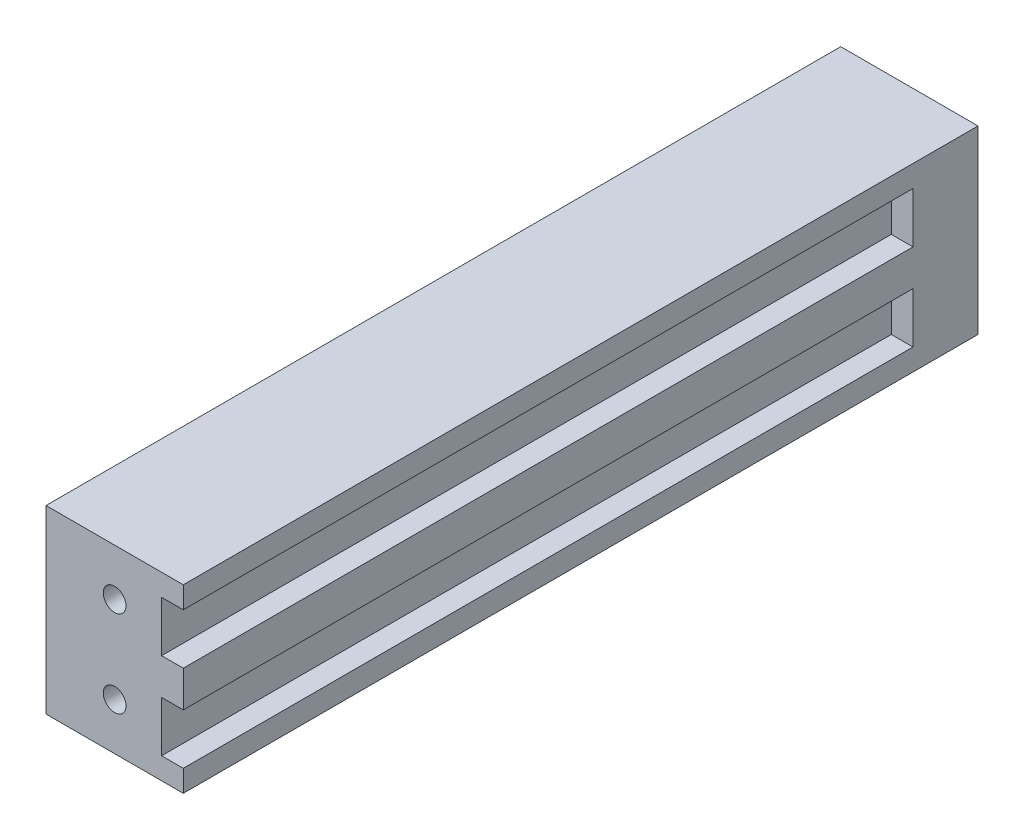
SolidWorks part; units mm, degrees
ref_plane "Ebene vorne" through (0, 0, 0) normal (0, 0, 1) x (1, 0, 0)
ref_plane "Ebene oben" through (0, 0, 0) normal (0, 1, 0) x (1, 0, 0)
ref_plane "Ebene rechts" through (0, 0, 0) normal (1, 0, 0) x (0, 0, -1)
sketch "Sketch1" plane through (0, 0, 0) normal (0, 1, 0) x (1, 0, 0)
  line L1 (9.5, -55) -> (-9.5, -55)
  line L2 (9.5, -55) -> (9.5, 55)
  line L3 (9.5, 55) -> (-9.5, 55)
  line L4 (-9.5, -55) -> (-9.5, 55)
  line L5 (9.5, -55) -> (-9.5, 55) construction
  line L6 (9.5, 55) -> (-9.5, -55) construction
  point P0 (0, 0)
  dimension "D1" = 19
  dimension "D2" = 110
extrude "Block" add sketch "Sketch1" along normal blind 25
sketch "Sketch2" plane through (9.5, 0, 0) normal (1, 0, 0) x (0, 0, -1)
  line L0 (-55, 25) -> (-55, 0) construction
  line L1 (-55, 10) -> (46, 10)
  line L2 (-55, 10) -> (-55, 3)
  line L3 (-55, 3) -> (46, 3)
  line L4 (46, 10) -> (46, 3)
  line L5 (-55, 25) -> (55, 25) construction
  line L6 (-55, 0) -> (55, 0) construction
  line L7 (-55, 22) -> (46, 22)
  line L8 (-55, 22) -> (-55, 15)
  line L9 (-55, 15) -> (46, 15)
  line L10 (46, 22) -> (46, 15)
  dimension "D1" = 7
  dimension "D2" = 3
  dimension "D3" = 3
  dimension "D4" = 101
extrude "Slides" cut sketch "Sketch2" against normal blind 3
sketch "Sketch3" plane through (-9.5, 0, 0) normal (-1, 0, 0) x (0, 0, 1)
  line L0 (55, 25) -> (55, 0) construction
  line L2 (-55, 0) -> (55, 0) construction
  circle A0 centre (-50, 6) radius 1.5
  circle A1 centre (51, 6) radius 1.5
  dimension "D2" = 3
  dimension "D1" = 101
  dimension "D3" = 4
  dimension "D4" = 6
extrude "Mounting Holes" cut sketch "Sketch3" against normal blind 10
sketch "Sketch5" plane through (0, 0, 55) normal (0, 0, 1) x (1, 0, 0)
  line L0 (0, 25) -> (0, 0) construction
  line L1 (-9.5, 0) -> (9.5, 0) construction
  line L3 (-9.5, 25) -> (9.5, 25) construction
  line L4 (0, 12.5) -> (-5.3784, 12.5) construction
  circle A0 centre (0, 18.5) radius 1.575
  circle A1 centre (0, 6.5) radius 1.575
  dimension "D1" = 3.15
  dimension "D2" = 6
extrude "Cut-Extrude1" cut sketch "Sketch5" against normal blind 15 draft 1
equation "\"PCB\"=98"
equation "\"WithCase\"= 101"
equation "\"D4@Sketch2\"=\"WithCase\""
